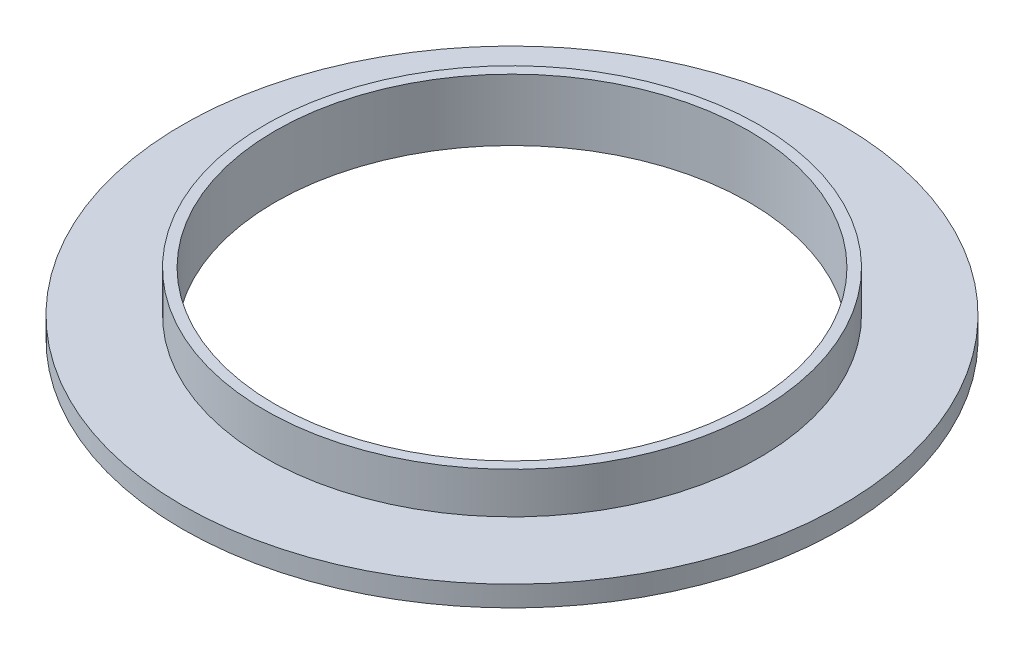
SolidWorks part; units mm, degrees
other "Markup1"
sketch "Sketch2" plane through (15, 3, 15) normal (0.008, 0.2858, 0.9582) x (0.9997, -0.0243, -0.0011)
ref_plane "Front Plane" through (0, 0, 0) normal (0, 0, 1) x (1, 0, 0)
ref_plane "Top Plane" through (0, 0, 0) normal (0, 1, 0) x (1, 0, 0)
ref_plane "Right Plane" through (0, 0, 0) normal (1, 0, 0) x (0, 0, -1)
sketch "Sketch1" plane through (0, 0, 0) normal (0, 0, 1) x (1, 0, 0)
  line L0 (0, 0) -> (0, 20.2788) construction
  line L1 (-11.5, 0) -> (-16, 0)
  line L2 (-16, 0) -> (-16, 1)
  line L3 (-16, 1) -> (-12, 1)
  line L6 (-12, 1) -> (-12, 3)
  line L7 (-12, 3) -> (-11.5, 3)
  line L8 (-11.5, 3) -> (-11.5, 0)
  dimension "D1" = 11.5
  dimension "D2" = 4.5
  dimension "D3" = 0.5
  dimension "D4" = 2
  dimension "D5" = 1
revolve "Revolve1" add sketch "Sketch1" angle 360 about L0
